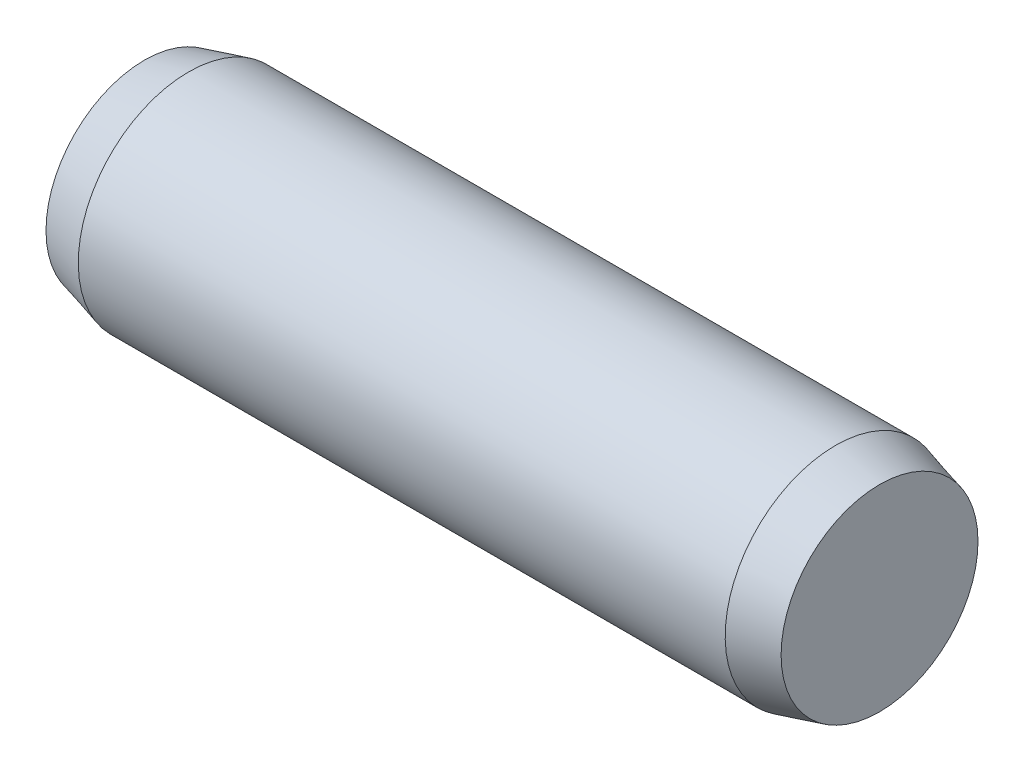
SolidWorks part; units mm, degrees
ref_plane "Přední rovina" through (0, 0, 0) normal (0, 0, 1) x (1, 0, 0)
ref_plane "Vrchní rovina" through (0, 0, 0) normal (0, 1, 0) x (1, 0, 0)
ref_plane "Pravá rovina" through (0, 0, 0) normal (1, 0, 0) x (0, 0, -1)
sketch "Skica1" plane through (0, 0, 0) normal (0, 0, 1) x (1, 0, 0)
  line L0 (0, 0) -> (0, 0.2678)
  line L1 (0, 0.2678) -> (0.12, 0.3)
  line L2 (0.12, 0.3) -> (1.88, 0.3)
  line L3 (1.88, 0.3) -> (2, 0.2678)
  line L4 (2, 0.2678) -> (2, 0)
  line L5 (2, 0) -> (0, 0)
  line L7 (1, 0.3) -> (1, 0) construction
  line L8 (0, 0) -> (-2, 0) construction
  dimension "D1" = 15
  dimension "D2" = 0.6
  dimension "c" = 0.12
  dimension "l" = 2
revolve "Otočit kolem osy1" add sketch "Skica1" angle 360 about L5
